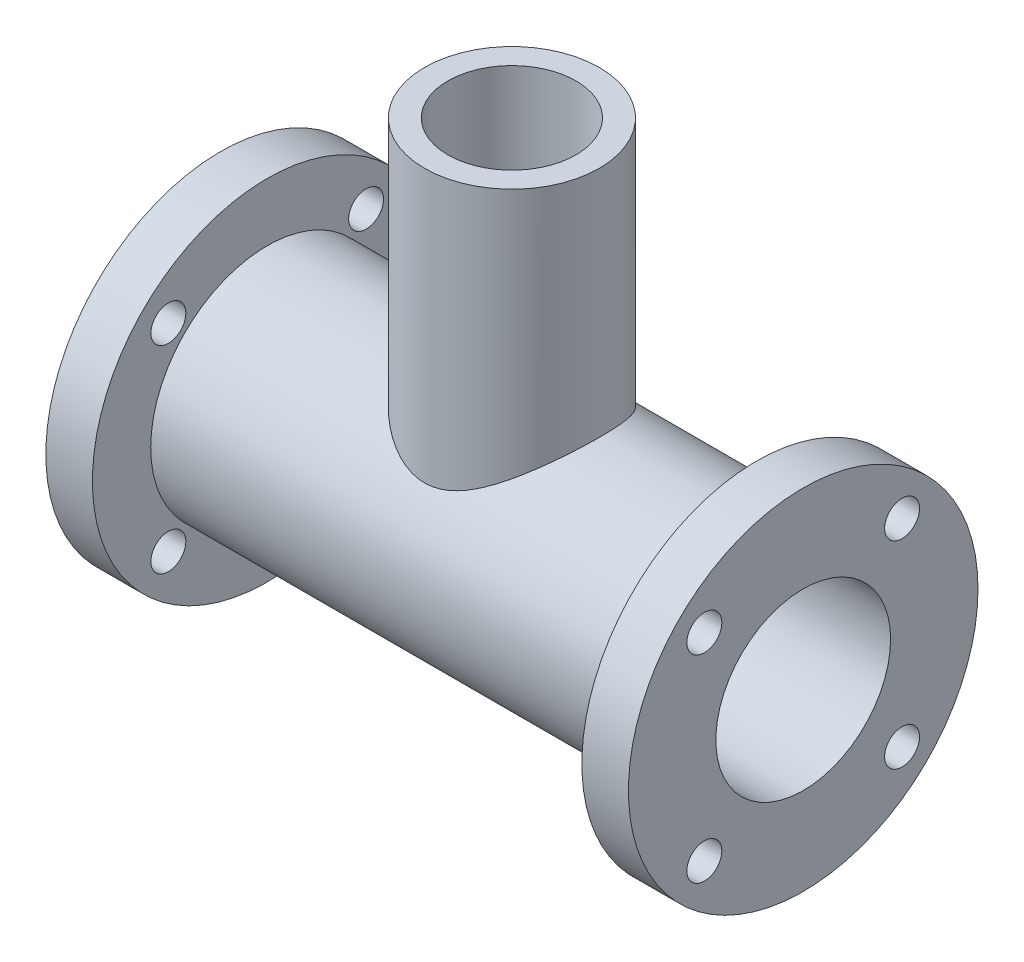
SolidWorks part; units mm, degrees
ref_plane "前视基准面" through (0, 0, 0) normal (0, 0, 1) x (1, 0, 0)
ref_plane "上视基准面" through (0, 0, 0) normal (0, 1, 0) x (1, 0, 0)
ref_plane "右视基准面" through (0, 0, 0) normal (1, 0, 0) x (0, 0, -1)
ref_plane "基准面1" through (-50, 0, 0) normal (1, 0, 0) x (0, 0, -1)
sketch "草图1" plane through (-50, 0, 0) normal (1, 0, 0) x (0, 0, -1)
  circle A0 centre (0, 0) radius 20
extrude "凸台-拉伸1" add sketch "草图1" along normal blind 100
sketch "草图2" plane through (-50, 0, 0) normal (1, 0, 0) x (0, 0, -1)
  circle A0 centre (0, 0) radius 30
extrude "凸台-拉伸2" add sketch "草图2" along normal blind 8
ref_plane "基准面2" through (42, 0, 0) normal (1, 0, 0) x (0, 0, -1)
sketch "草图3" plane through (42, 0, 0) normal (1, 0, 0) x (0, 0, -1)
  circle A0 centre (0, 0) radius 30
extrude "凸台-拉伸3" add sketch "草图3" along normal blind 8
sketch "草图4" plane through (0, 0, 0) normal (0, 1, 0) x (1, 0, 0)
  circle A0 centre (0, 0) radius 15
extrude "凸台-拉伸4" add sketch "草图4" along normal blind 60
sketch "草图5" plane through (-50, 0, 0) normal (1, 0, 0) x (0, 0, -1)
  circle A0 centre (0, 0) radius 15
extrude "切除-拉伸1" cut sketch "草图5" along normal through all
ref_plane "基准面3" through (0, 60, 0) normal (0, 1, 0) x (1, 0, 0)
sketch "草图7" plane through (0, 60, 0) normal (0, 1, 0) x (1, 0, 0)
  circle A0 centre (0, 0) radius 11
extrude "切除-拉伸3" cut sketch "草图7" against normal blind 60
sketch "草图8" plane through (-50, 0, 0) normal (1, 0, 0) x (0, 0, -1)
  circle A0 centre (-16.9706, 16.9706) radius 3
  circle A1 centre (16.9706, 16.9706) radius 3
  circle A2 centre (16.9706, -16.9706) radius 3
  circle A3 centre (-16.9706, -16.9706) radius 3
extrude "切除-拉伸4" cut sketch "草图8" along normal blind 8
ref_plane "基准面4" through (50, 0, 0) normal (1, 0, 0) x (0, 0, -1)
sketch "草图9" plane through (50, 0, 0) normal (1, 0, 0) x (0, 0, -1)
  circle A0 centre (-16.9706, 16.9706) radius 3
  circle A1 centre (16.9706, 16.9706) radius 3
  circle A2 centre (16.9706, -16.9706) radius 3
  circle A3 centre (-16.9706, -16.9706) radius 3
extrude "切除-拉伸5" cut sketch "草图9" against normal blind 8
